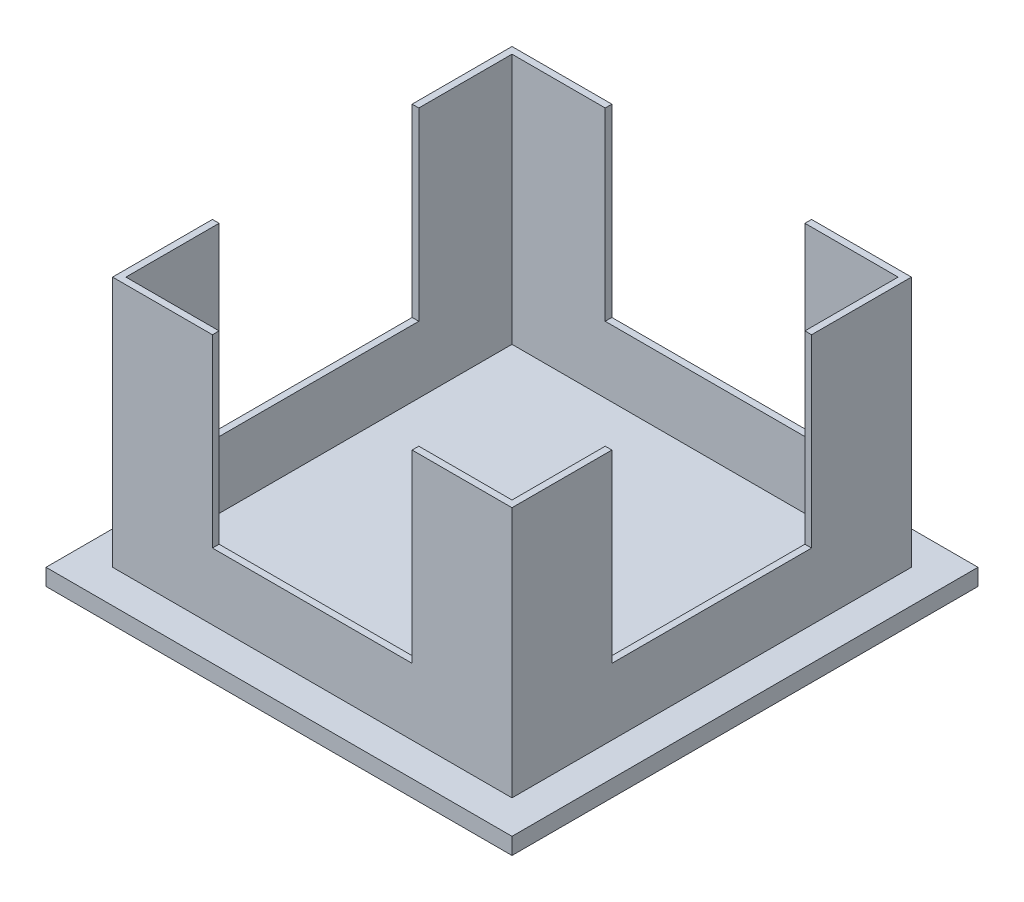
SolidWorks part; units mm, degrees
ref_plane "Front Plane" through (0, 0, 0) normal (0, 0, 1) x (1, 0, 0)
ref_plane "Top Plane" through (0, 0, 0) normal (0, 1, 0) x (1, 0, 0)
ref_plane "Right Plane" through (0, 0, 0) normal (1, 0, 0) x (0, 0, -1)
sketch "Sketch1" plane through (0, 0, 0) normal (0, 1, 0) x (1, 0, 0)
  line L1 (-70, -70) -> (70, -70)
  line L2 (-70, -70) -> (-70, 70)
  line L3 (-70, 70) -> (70, 70)
  line L4 (70, -70) -> (70, 70)
  line L5 (-70, -70) -> (70, 70) construction
  line L6 (-70, 70) -> (70, -70) construction
  circle A0 centre (0, 0) radius 10.5
  point P0 (0, 0)
  dimension "D3" = 21
  dimension "D1" = 140
  dimension "D2" = 140
extrude "Boss-Extrude1" add sketch "Sketch1" along normal blind 5
sketch "Sketch2" plane through (0, 5, 0) normal (0, 1, 0) x (1, 0, 0)
  line L1 (-60, -60) -> (60, -60)
  line L8 (-60, -60) -> (-60, 60)
  line L9 (-60, 60) -> (60, 60)
  line L23 (60, -60) -> (60, 60)
  line L24 (-60, -60) -> (60, 60) construction
  line L25 (-60, 60) -> (60, -60) construction
  line L26 (-58, -58) -> (58, -58)
  line L27 (-58, -58) -> (-58, 58)
  line L28 (-58, 58) -> (58, 58)
  line L29 (58, -58) -> (58, 58)
  line L30 (-58, -58) -> (58, 58) construction
  line L31 (-58, 58) -> (58, -58) construction
  point P0 (0, 0)
  point P5 (0, 0)
  dimension "D1" = 2
  dimension "D2" = 120
extrude "Boss-Extrude2" add sketch "Sketch2" along normal blind 75.5
sketch "Sketch4" plane through (0, 0, 0) normal (0, 0, -1) x (-1, 0, 0)
  line L0 (-60, 80.5) -> (60, 80.5) construction
  line L1 (30, 80.5) -> (-30, 80.5)
  line L2 (30, 80.5) -> (30, 25)
  line L3 (30, 25) -> (-30, 25)
  line L4 (-30, 80.5) -> (-30, 25)
  line L5 (0, 25) -> (0, 89.6462) construction
  line L6 (-60, 80.5) -> (-60, 5) construction
  line L7 (60, 80.5) -> (60, 5) construction
  line L8 (30, 25) -> (30, 5) construction
  line L9 (-60, 5) -> (60, 5) construction
  line L10 (30, 80.5) -> (60, 80.5) construction
  dimension "D1" = 60
  dimension "D2" = 20
extrude "Cut-Extrude1" cut sketch "Sketch4" against normal through all both and the other way through all
sketch "Sketch6" plane through (0, 0, 0) normal (1, 0, 0) x (0, 0, -1)
  line L0 (-60, 80.5) -> (60, 80.5) construction
  line L5 (-30, 80.5) -> (30, 80.5)
  line L6 (-30, 80.5) -> (-30, 25)
  line L7 (-30, 25) -> (30, 25)
  line L8 (30, 80.5) -> (30, 25)
  line L9 (0, 25) -> (0, 80.5) construction
  line L10 (-60, 80.5) -> (-60, 5) construction
  line L11 (60, 80.5) -> (60, 5) construction
  line L12 (-60, 5) -> (60, 5) construction
  dimension "D1" = 60
  dimension "D2" = 20
extrude "Cut-Extrude2" cut sketch "Sketch6" against normal through all both and the other way through all
